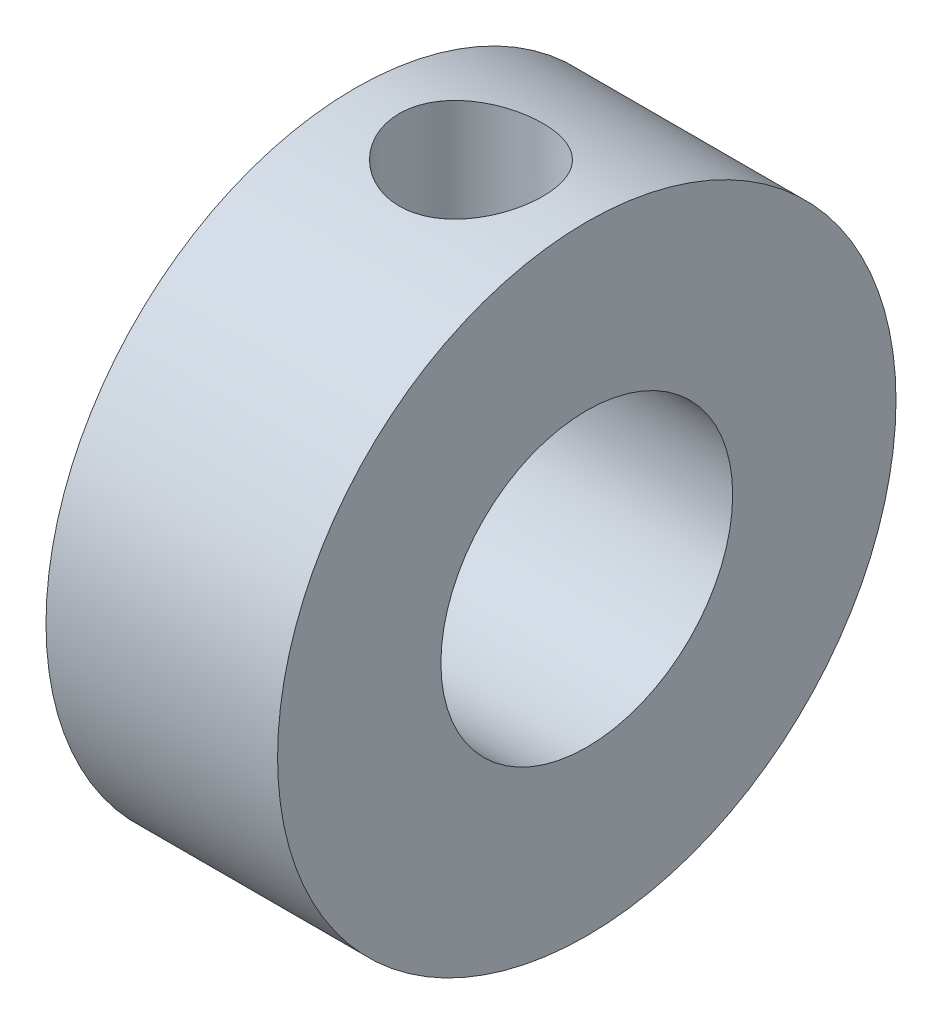
SolidWorks part; units mm, degrees
ref_plane "Front Plane" through (0, 0, 0) normal (0, 0, 1) x (1, 0, 0)
ref_plane "Top Plane" through (0, 0, 0) normal (0, 1, 0) x (1, 0, 0)
ref_plane "Right Plane" through (0, 0, 0) normal (1, 0, 0) x (0, 0, -1)
sketch "Sketch1" plane through (0, 0, 0) normal (0, 0, 1) x (1, 0, 0)
  line L0 (0, 8.001) -> (0, 16.9581)
  line L1 (0, 16.9581) -> (12.7, 16.9581)
  line L2 (12.7, 16.9581) -> (12.7, 8.001)
  line L3 (12.7, 8.001) -> (0, 8.001)
  point P0 (0, 16.9581)
  point P1 (0, 8.001)
  point P6 (12.7, 16.9581)
sketch3d "3DSketch1"
  line L0 (0, 0, 0) -> (109, 0, 0) construction
revolve "Revolve1" add sketch "Sketch1" angle 360 about L0
hole_wizard "Hole2" positions "3DSketch4" profile "Sketch4" legacy
sketch3d "3DSketch4"
  point P0 (6.35, 16.9581, 0)
sketch "Sketch4" plane through (6.35, 16.9581, 0) normal (1, 0, 0) x (0, 0, 1)
  line L0 (0, 0) -> (0, 17.78)
  line L1 (0, 17.78) -> (3.937, 17.78)
  line L2 (3.937, 17.78) -> (3.937, 0)
  line L3 (3.937, 0) -> (0, 0)
  line L4 (0, 110) -> (0, -10) construction
  dimension "Diameter" = 7.874
  dimension "Depth" = 17.78
